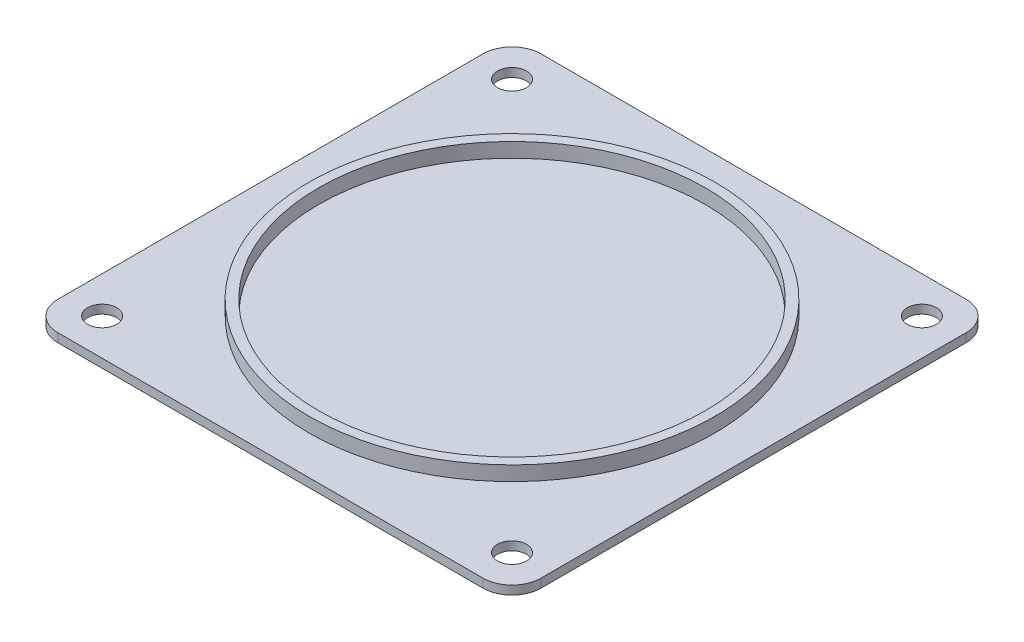
SolidWorks part; units mm, degrees
ref_plane "Front Plane" through (0, 0, 0) normal (0, 0, 1) x (1, 0, 0)
ref_plane "Top Plane" through (0, 0, 0) normal (0, 1, 0) x (1, 0, 0)
ref_plane "Right Plane" through (0, 0, 0) normal (1, 0, 0) x (0, 0, -1)
sketch "Sketch2" plane through (0, 0, 0) normal (0, 1, 0) x (1, 0, 0)
  line L1 (-50, 50) -> (50, 50)
  line L2 (-50, 50) -> (-50, -50)
  line L3 (-50, -50) -> (50, -50)
  line L4 (50, 50) -> (50, -50)
  circle A0 centre (-42.425, 42.425) radius 3
  circle A1 centre (42.425, 42.425) radius 3
  circle A2 centre (42.425, -42.425) radius 3
  circle A3 centre (-42.425, -42.425) radius 3
  point P0 (0, 0)
  point P6 (0, 0)
  point P8 (-42.5754, 42.5754)
  point P15 (42.5754, 42.5754)
  point P23 (-42.5754, -42.5754)
  point P31 (42.5754, -42.5754)
  dimension "D5" = 6
  dimension "D1" = 100
  dimension "D2" = 100
  dimension "D3" = 84.85
  dimension "D4" = 84.85
extrude "Boss-Extrude1" add sketch "Sketch2" along normal blind 1.8
fillet "Fillet1" radius 6 4 edges at (-50, 0.9, 50) (-50, 0.9, -50) (50, 0.9, -50) (50, 0.9, 50)
sketch "Sketch3" plane through (0, 1.8, 0) normal (0, 1, 0) x (1, 0, 0)
  circle A0 centre (0, 0) radius 42
  circle A1 centre (0, 0) radius 40
  dimension "D1" = 84
  dimension "D2" = 80
extrude "Boss-Extrude2" add sketch "Sketch3" along normal blind 3
